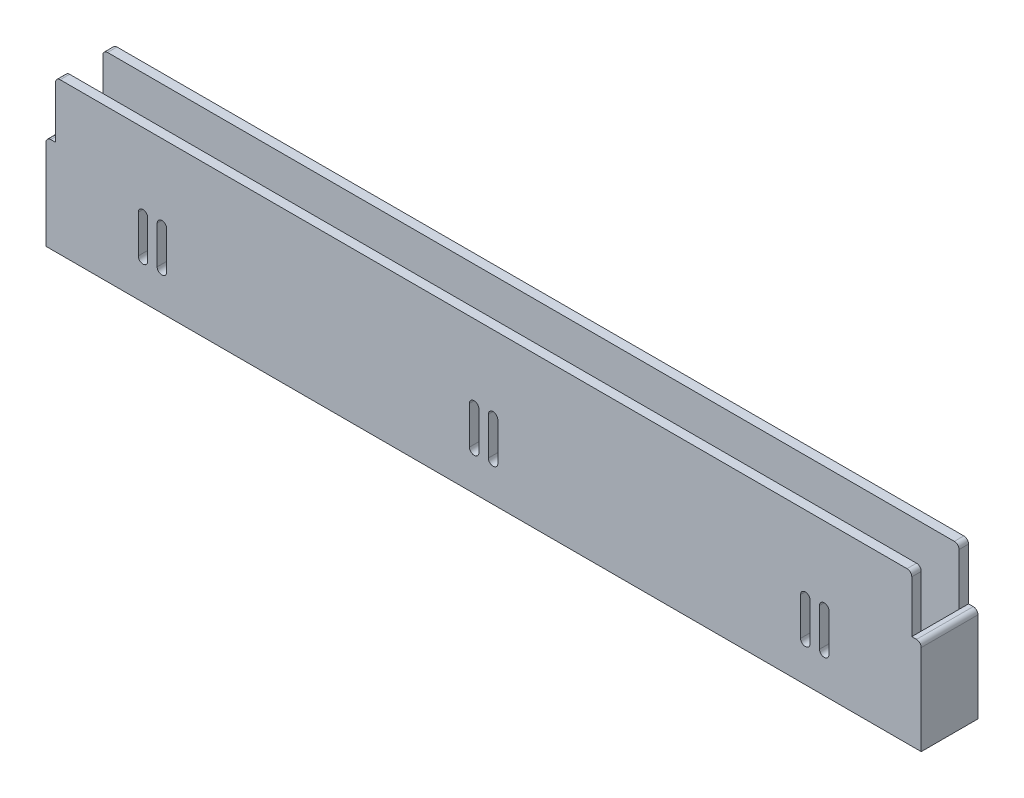
SolidWorks part; units mm, degrees
ref_plane "前视基准面" through (0, 0, 0) normal (0, 0, 1) x (1, 0, 0)
ref_plane "上视基准面" through (0, 0, 0) normal (0, 1, 0) x (1, 0, 0)
ref_plane "右视基准面" through (0, 0, 0) normal (1, 0, 0) x (0, 0, -1)
other "Configuration Table"
sketch "草图1" plane through (0, 0, 0) normal (0, 0, 1) x (1, 0, 0)
  line L0 (0, 0) -> (181, 0)
  line L1 (181, 0) -> (181, 30)
  line L2 (181, 30) -> (0, 30)
  line L3 (0, 30) -> (0, 0)
  dimension "D1" = 30
  dimension "D2" = 181
extrude "凸台-拉伸1" add sketch "草图1" along normal blind 2
sketch "草图2" plane through (0, 0, 0) normal (0, 0, 1) x (1, 0, 0)
  line L0 (0, 0) -> (0, -2)
  line L1 (0, -2) -> (181, -2)
  line L2 (181, -2) -> (181, 0)
  line L3 (181, 0) -> (0, 0)
extrude "凸台-拉伸2" add sketch "草图2" along normal blind 10
ref_plane "基准面1" through (0, 0, 10) normal (0, 0, 1) x (1, 0, 0)
sketch "草图3" plane through (0, 0, 10) normal (0, 0, 1) x (1, 0, 0)
  line L0 (0, -2) -> (0, 30)
  line L1 (0, 30) -> (181, 30)
  line L2 (181, 30) -> (181, -2)
  line L3 (181, -2) -> (0, -2)
extrude "凸台-拉伸3" add sketch "草图3" along normal blind 2
sketch "草图4" plane through (0, 0, 12) normal (0, 0, 1) x (1, 0, 0)
  line L0 (90.5, -2) -> (90.5, 10)
  line L1 (0, -2) -> (181, -2) construction
  line L2 (90.5, 10) -> (20.5, 10)
  line L3 (90.5, 10) -> (160.5, 10)
  line L4 (20.5, 10) -> (21.5, 10)
  line L5 (20.5, 10) -> (19.49, 10)
  line L6 (18.5, 14) -> (18.5, 6) construction
  line L7 (20.5, 10) -> (20.5, 14)
  line L8 (17.5, 14) -> (17.5, 6)
  line L9 (19.5, 14) -> (19.5, 6)
  line L10 (21.5, 14) -> (22.5, 14)
  line L11 (21.5, 6) -> (22.5, 6)
  line L12 (22.5, 14) -> (22.5, 6) construction
  line L13 (23.5, 14) -> (23.5, 6)
  line L14 (21.5, 14) -> (21.5, 6)
  line L15 (92.5, 14) -> (92.5, 6) construction
  line L16 (93.5, 14) -> (93.5, 6)
  line L17 (91.5, 14) -> (91.5, 6)
  line L18 (88.5, 14) -> (88.5, 6) construction
  line L19 (87.5, 14) -> (87.5, 6)
  line L20 (89.5, 14) -> (89.5, 6)
  line L21 (162.5, 14) -> (162.5, 6) construction
  line L22 (163.5, 14) -> (163.5, 6)
  line L23 (161.5, 14) -> (161.5, 6)
  line L24 (158.5, 14) -> (158.5, 6) construction
  line L25 (157.5, 14) -> (157.5, 6)
  line L26 (159.5, 14) -> (159.5, 6)
  arc A1 (23.5, 14) -> (21.5, 14) centre (22.5, 14) ccw
  arc A2 (21.5, 6) -> (23.5, 6) centre (22.5, 6) ccw
  arc A3 (17.5, 14) -> (19.5, 14) centre (18.5, 14) cw
  arc A4 (19.5, 6) -> (17.5, 6) centre (18.5, 6) cw
  arc A5 (93.5, 14) -> (91.5, 14) centre (92.5, 14) ccw
  arc A6 (91.5, 6) -> (93.5, 6) centre (92.5, 6) ccw
  arc A7 (87.5, 14) -> (89.5, 14) centre (88.5, 14) cw
  arc A8 (89.5, 6) -> (87.5, 6) centre (88.5, 6) cw
  arc A9 (163.5, 14) -> (161.5, 14) centre (162.5, 14) ccw
  arc A10 (161.5, 6) -> (163.5, 6) centre (162.5, 6) ccw
  arc A11 (157.5, 14) -> (159.5, 14) centre (158.5, 14) cw
  arc A12 (159.5, 6) -> (157.5, 6) centre (158.5, 6) cw
  point P7 (22.5, 10)
  point P20 (18.5, 10)
  point P27 (92.5, 10)
  point P36 (88.5, 10)
  point P41 (162.5, 10)
  point P50 (158.5, 10)
  dimension "D1" = 70
  dimension "D2" = 1
  dimension "D3" = 8
  dimension "D5" = 12
  dimension "D4" = 3
extrude "切除-拉伸1" cut sketch "草图4" against normal blind 2
sketch "草图5" plane through (0, 0, 0) normal (1, 0, 0) x (0, 0, -1)
  line L0 (-12, -2) -> (0, -2)
  line L1 (0, -2) -> (0, 18.0574)
  line L2 (0, -2) -> (0, 30) construction
  line L3 (0, 18.0574) -> (-12, 18.0574)
  line L5 (-12, 18.0574) -> (-12, -2)
extrude "凸台-拉伸4" add sketch "草图5" against normal blind 2
ref_plane "基准面2" through (181, 0, 0) normal (1, 0, 0) x (0, 0, -1)
sketch "草图6" plane through (181, 0, 0) normal (1, 0, 0) x (0, 0, -1)
  line L0 (0, -2) -> (0, 18.0574)
  line L1 (0, 18.0574) -> (-12, 18.0574)
  line L2 (-12, 18.0574) -> (-12, -2)
  line L3 (-12, -2) -> (0, -2)
extrude "凸台-拉伸5" add sketch "草图6" along normal blind 2
fillet "圆角1" radius 1 6 edges at (-2, 18.0574, 6) (183, 18.0574, 6) (181, 30, 11) (0, 30, 11) (0, 30, 1) (181, 30, 1)
